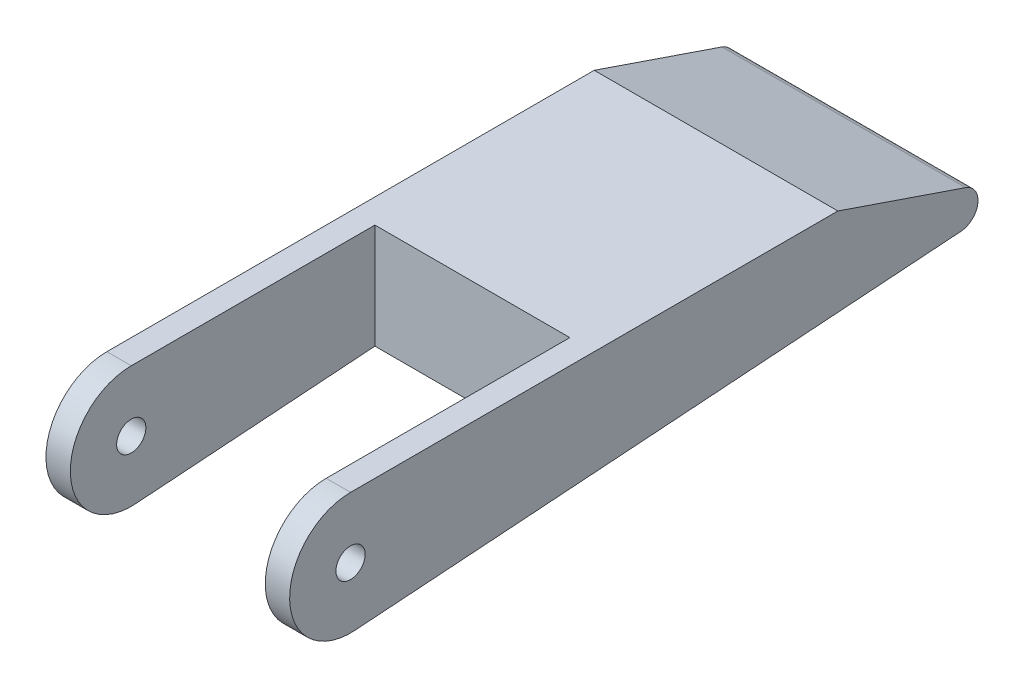
SolidWorks part; units mm, degrees
material "ABS"
ref_plane "Front Plane" through (0, 0, 0) normal (0, 0, 1) x (1, 0, 0)
ref_plane "Top Plane" through (0, 0, 0) normal (0, 1, 0) x (1, 0, 0)
ref_plane "Right Plane" through (0, 0, 0) normal (1, 0, 0) x (0, 0, -1)
sketch "Sketch1" plane through (0, 0, 0) normal (1, 0, 0) x (0, 0, -1)
  line L0 (0, 10) -> (80, 10)
  line L1 (80, 10) -> (100.9695, 2.839)
  line L2 (100.21, -2.9926) -> (80, -4.4108)
  line L3 (80, -4.4108) -> (0.7, -9.9755)
  circle A0 centre (0, 0) radius 2.4
  arc A1 (0, 10) -> (0.7, -9.9755) centre (0, 0) ccw
  arc A2 (100.9695, 2.839) -> (100.21, -2.9926) centre (100, 0) cw
  point P10 (0, 0)
  point P11 (78.1011, -4.8793)
  point P12 (0, 0)
  point P13 (80, -5)
  point P14 (2.2934, -9.7335)
  point P15 (0, 0)
  dimension "D1" = 4.8
  dimension "D2" = 3
  dimension "D3" = 10
  dimension "D4" = 80
  dimension "D6" = 20
extrude "arm" add sketch "Sketch1" along normal mid plane 40
sketch "Sketch2" plane through (0, 0, 0) normal (0, 1, 0) x (1, 0, 0)
  line L0 (0, 0) -> (0, 49954.0105) construction
  line L1 (-20, -10) -> (20, -10) construction
  line L2 (-16, 40) -> (16, 40)
  line L3 (-16, 40) -> (-16, -10)
  line L4 (-16, -10) -> (16, -10)
  line L5 (16, 40) -> (16, -10)
  line L6 (-16, 40) -> (16, -10) construction
  line L7 (-16, -10) -> (16, 40) construction
  line L8 (20, 80) -> (20, 0) construction
  point P3 (0, 15)
  dimension "D1" = 4
  dimension "D2" = 50
extrude "elbow mount" cut sketch "Sketch2" against normal through all both and the other way through all
equation "\"D1@Sketch1\"=2*2.4mm"
